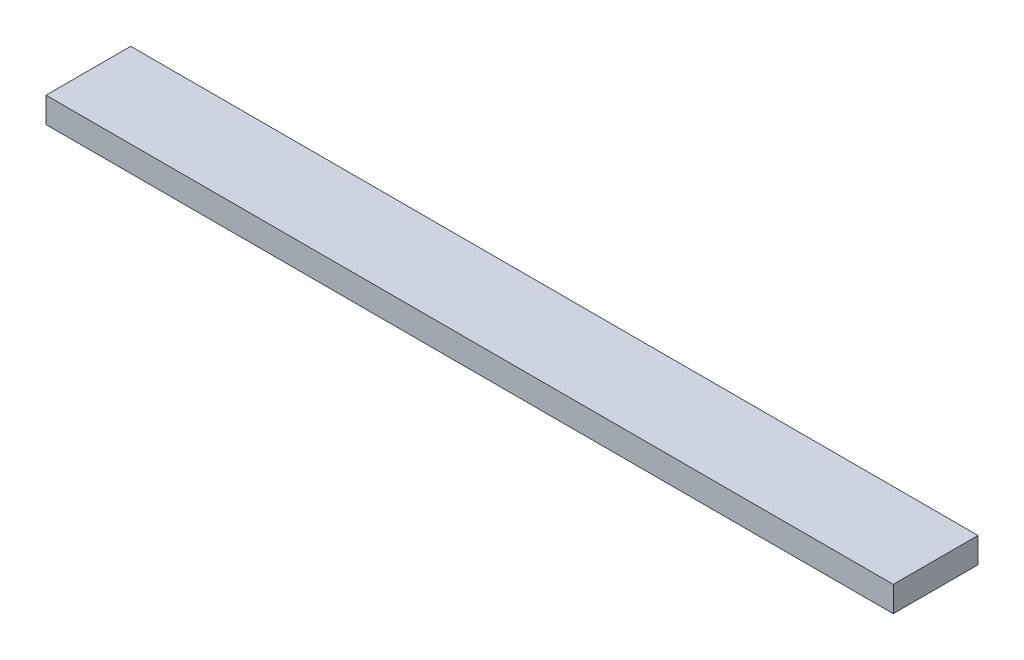
SolidWorks part; units mm, degrees
material "Pine"
ref_plane "Front Plane" through (0, 0, 0) normal (0, 0, 1) x (1, 0, 0)
ref_plane "Top Plane" through (0, 0, 0) normal (0, 1, 0) x (1, 0, 0)
ref_plane "Right Plane" through (0, 0, 0) normal (1, 0, 0) x (0, 0, -1)
sketch "Sketch1" plane through (0, 0, 0) normal (0, 1, 0) x (1, 0, 0)
  line L1 (0, 0) -> (200, 0)
  line L2 (0, 0) -> (0, 20)
  line L3 (0, 20) -> (200, 20)
  line L4 (200, 0) -> (200, 20)
  dimension "D1" = 200
  dimension "D2" = 20
extrude "Boss-Extrude1" add sketch "Sketch1" along normal blind 6
equation "\"BoardThickness\"= 6"
equation "\"D1@Boss-Extrude1\"=\"BoardThickness\""
